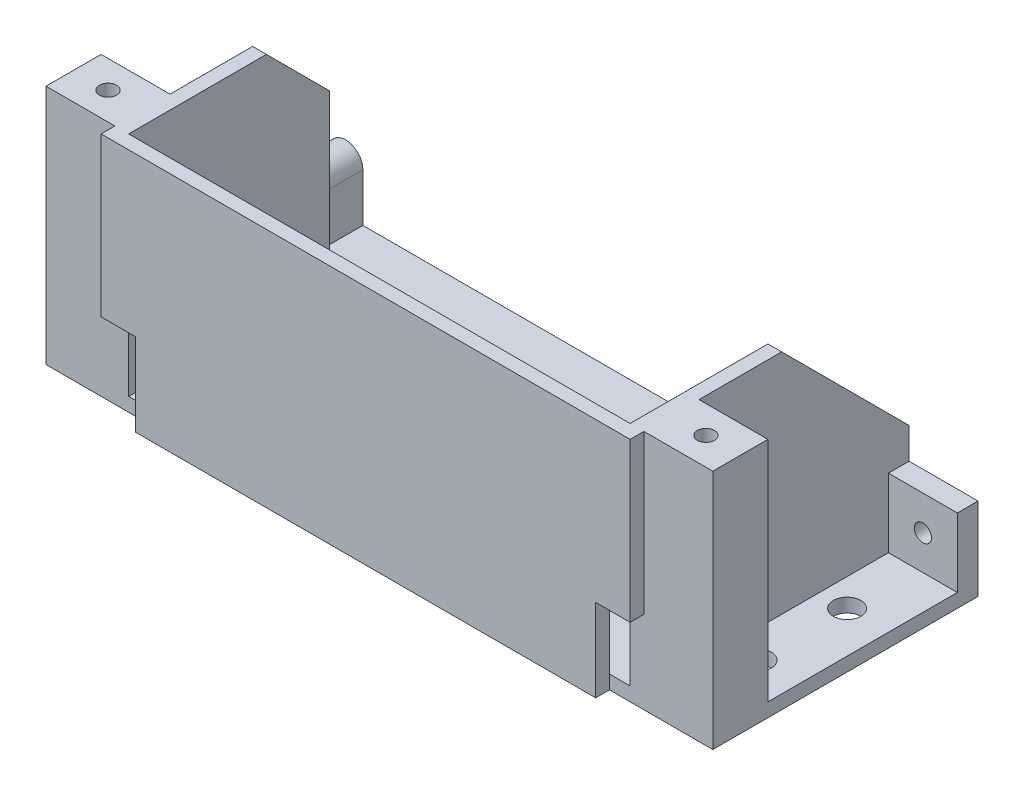
SolidWorks part; units mm, degrees
ref_plane "Alzado" through (0, 0, 0) normal (0, 0, 1) x (1, 0, 0)
ref_plane "Planta" through (0, 0, 0) normal (0, 1, 0) x (1, 0, 0)
ref_plane "Vista lateral" through (0, 0, 0) normal (1, 0, 0) x (0, 0, -1)
sketch "Croquis1" plane through (0, 0, 0) normal (0, 1, 0) x (1, 0, 0)
  line L1 (-48.4, 20.25) -> (48.4, 20.25)
  line L2 (-48.4, 20.25) -> (-48.4, -20.25)
  line L3 (-48.4, -20.25) -> (48.4, -20.25)
  line L4 (48.4, 20.25) -> (48.4, -20.25)
  line L5 (-48.4, 20.25) -> (48.4, -20.25) construction
  line L6 (-48.4, -20.25) -> (48.4, 20.25) construction
  point P0 (0, 0)
  dimension "D1" = 40.5
  dimension "D2" = 96.8
extrude "Saliente-Extruir1" add sketch "Croquis1" along normal blind 2
sketch "Croquis2" plane through (0, 2, 0) normal (0, 1, 0) x (1, 0, 0)
  line L0 (0, -20.25) -> (0, -10.7277) construction
  line L1 (-48.4, -20.25) -> (-33.4, -20.25)
  line L2 (-48.4, -20.25) -> (-48.4, -18.25)
  line L3 (-48.4, -18.25) -> (-33.4, -18.25)
  line L4 (-33.4, -20.25) -> (-33.4, -18.25)
  line L5 (-48.4, -20.25) -> (48.4, -20.25) construction
  line L6 (33.4, -20.25) -> (33.4, -18.25)
  line L7 (48.4, -18.25) -> (33.4, -18.25)
  line L8 (48.4, -20.25) -> (48.4, -18.25)
  line L9 (48.4, -20.25) -> (33.4, -20.25)
  dimension "D1" = 2
  dimension "D2" = 15
sketch "Croquis4" plane through (0, 2, 0) normal (0, 1, 0) x (1, 0, 0)
  line L0 (-48.4, -20.25) -> (48.4, -20.25) construction
  line L1 (-38.4, 20.25) -> (38.4, 20.25)
  line L2 (-38.4, 20.25) -> (-38.4, -20.25)
  line L3 (-38.4, -20.25) -> (38.4, -20.25)
  line L4 (38.4, 20.25) -> (38.4, -20.25)
  line L5 (-38.4, 20.25) -> (38.4, -20.25) construction
  line L6 (-38.4, -20.25) -> (38.4, 20.25) construction
  line L7 (48.4, -20.25) -> (48.4, 20.25) construction
  line L8 (-36.4, 18.25) -> (36.4, 18.25)
  line L9 (-36.4, 18.25) -> (-36.4, -18.25)
  line L10 (-36.4, -18.25) -> (36.4, -18.25)
  line L11 (36.4, 18.25) -> (36.4, -18.25)
  line L12 (-36.4, 18.25) -> (36.4, -18.25) construction
  line L13 (-36.4, -18.25) -> (36.4, 18.25) construction
  point P0 (0, 0)
  point P8 (0, 0)
  dimension "D1" = 10
  dimension "D2" = 2
  dimension "D3" = 2
extrude "Saliente-Extruir6" add sketch "Croquis4" along normal blind 33
extrude "Cortar-Extruir2" cut sketch "Croquis2" against normal blind 12 from offset 10
sketch "Croquis5" plane through (38.4, 0, 0) normal (1, 0, 0) x (0, 0, -1)
  line L0 (1.75, 35) -> (20.25, 16.5)
  line L1 (-20.25, 35) -> (20.25, 35) construction
  line L2 (20.25, 35) -> (20.25, 2) construction
  line L3 (-20.25, 35) -> (-20.25, 12) construction
  line L4 (1.75, 35) -> (20.25, 35)
  line L5 (20.25, 35) -> (20.25, 16.5)
  dimension "D1" = 22
  dimension "D2" = 45
sketch "Croquis6" plane through (0, 35, 0) normal (0, 1, 0) x (1, 0, 0)
  line L0 (36.4, 18.25) -> (-36.4, 18.25)
  line L1 (-36.4, 18.25) -> (-36.4, 10.9097)
  line L2 (-36.4, 18.25) -> (-36.4, -18.25) construction
  line L3 (-36.4, 10.9097) -> (-38.4, 10.9097)
  line L4 (-38.4, 20.25) -> (-38.4, -18.25) construction
  line L5 (-38.4, 10.9097) -> (-38.4, 20.25)
  line L6 (-38.4, 20.25) -> (36.4, 20.25)
  line L7 (38.4, 20.25) -> (-38.4, 20.25) construction
  line L8 (36.4, 20.25) -> (36.4, 18.25)
extrude "Cortar-Extruir4" cut sketch "Croquis6" against normal up to surface (33 mm away) up to face at (43.4, 2, -1)
extrude "Cortar-Extruir5" cut sketch "Croquis5" against normal through all
sketch "Croquis7" plane through (0, 2, 0) normal (0, 1, 0) x (1, 0, 0)
  line L0 (48.4, -18.25) -> (48.4, 20.25) construction
  line L1 (-48.4, 20.25) -> (-48.4, -18.25) construction
  line L2 (48.4, 20.25) -> (38.4, 20.25) construction
  line L3 (36.4, 20.25) -> (-48.4, 20.25) construction
  circle A0 centre (42.4, 7.25) radius 2
  circle A1 centre (42.4, -5.75) radius 2
  circle A2 centre (-42.9, 5.25) radius 2
  circle A3 centre (-42.9, -7.75) radius 2
  point P14 (0, 0)
  point P15 (0, 0)
  dimension "D1" = 4
  dimension "D2" = 6
  dimension "D3" = 5.5
  dimension "D4" = 13
  dimension "D5" = 26
  dimension "D6" = 15
  dimension "D7" = 28
extrude "Cortar-Extruir6" cut sketch "Croquis7" against normal blind 12
sketch "Croquis8" plane through (0, 2, 0) normal (0, 1, 0) x (1, 0, 0)
  line L0 (38.4, -18.25) -> (38.4, 20.25) construction
  line L1 (48.4, 20.25) -> (38.4, 20.25)
  line L2 (48.4, 20.25) -> (48.4, 17.25)
  line L3 (48.4, 17.25) -> (38.4, 17.25)
  line L4 (38.4, 20.25) -> (38.4, 17.25)
  line L5 (-48.4, 20.25) -> (-48.4, -18.25) construction
  line L6 (-38.4, 10.9097) -> (-48.4, 10.9097)
  line L7 (-38.4, 10.9097) -> (-38.4, 7.9097)
  line L8 (-38.4, 7.9097) -> (-48.4, 7.9097)
  line L9 (-48.4, 10.9097) -> (-48.4, 7.9097)
  dimension "D1" = 3
  dimension "D2" = 3
extrude "Saliente-Extruir7" add sketch "Croquis8" along normal blind 10
sketch "Croquis13" plane through (0, 0, -10.9097) normal (0, 0, -1) x (-1, 0, 0)
  line L0 (36.4, 2) -> (48.4, 2) construction
  line L1 (45.9, 2) -> (40.9, 2)
  line L2 (45.9, 2) -> (45.9, 9)
  line L4 (40.9, 2) -> (40.9, 9)
  line L5 (48.4, 12) -> (48.4, 2) construction
  arc A0 (45.9, 9) -> (40.9, 9) centre (43.4, 9) ccw
  point P8 (0, 0)
  dimension "D1" = 2.5
  dimension "D3" = 5
extrude "Saliente-Extruir9" add sketch "Croquis13" along normal up to surface (9.3403 mm away) up to face at (18.7, 7.625, -20.25)
sketch "Croquis9" plane through (0, 2, 0) normal (0, 1, 0) x (1, 0, 0)
  line L0 (-48.4, 7.9097) -> (-48.4, -18.25) construction
  line L1 (-38.4, -18.25) -> (-48.4, -18.25)
  line L2 (-38.4, -18.25) -> (-38.4, -10.25)
  line L3 (-38.4, -10.25) -> (-48.4, -10.25)
  line L4 (-48.4, -18.25) -> (-48.4, -10.25)
  line L5 (0, 0) -> (0, -33.2635) construction
  line L6 (48.4, -18.25) -> (48.4, -10.25)
  line L7 (38.4, -10.25) -> (48.4, -10.25)
  line L8 (38.4, -18.25) -> (38.4, -10.25)
  line L9 (38.4, -18.25) -> (48.4, -18.25)
  dimension "D1" = 8
extrude "Saliente-Extruir8" add sketch "Croquis9" along normal up to surface (33 mm away) up to face at (0, 35, 8.75)
sketch "Croquis10" plane through (0, 35, 0) normal (0, 1, 0) x (1, 0, 0)
  line L0 (-48.4, -10.25) -> (-38.4, -18.25) construction
  line L1 (-38.4, -18.25) -> (-48.4, -18.25) construction
  line L2 (-48.4, -18.25) -> (-38.4, -10.25) construction
  line L3 (-38.4, -10.25) -> (38.4, -10.25) construction
  line L4 (38.4, -10.25) -> (48.4, -18.25) construction
  line L5 (48.4, -18.25) -> (38.4, -18.25) construction
  line L6 (38.4, -18.25) -> (48.4, -10.25) construction
  circle A0 centre (-43.4, -14.25) radius 1.25
  circle A1 centre (43.4, -14.25) radius 1.25
  dimension "D1" = 2.5
  dimension "D2" = 2.5
extrude "Cortar-Extruir7" cut sketch "Croquis10" against normal blind 10
sketch "Croquis11" plane through (0, 0, -20.25) normal (0, 0, -1) x (-1, 0, 0)
  line L0 (0, 0) -> (0, 40.2674) construction
  line L1 (-48.4, 12) -> (-38.4, 12) construction
  line L2 (-48.4, 12) -> (-48.4, 0) construction
  circle A0 centre (-43.4, 7) radius 1.25
  circle A1 centre (43.4, 7) radius 1.25
  dimension "D1" = 2.5
  dimension "D2" = 5
  dimension "D3" = 5
extrude "Cortar-Extruir8" cut sketch "Croquis11" against normal up to surface (12.3403 mm away) up to face at (-43.4, 7, -7.9097)
